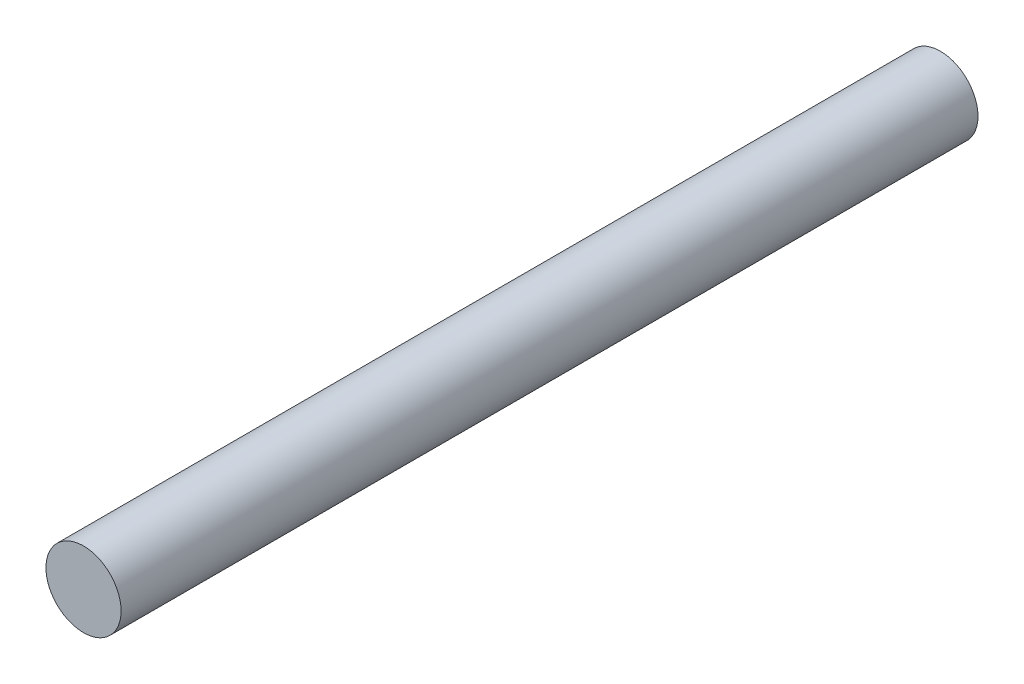
SolidWorks part; units mm, degrees
ref_plane "Front Plane" through (0, 0, 0) normal (0, 0, 1) x (1, 0, 0)
ref_plane "Top Plane" through (0, 0, 0) normal (0, 1, 0) x (1, 0, 0)
ref_plane "Right Plane" through (0, 0, 0) normal (1, 0, 0) x (0, 0, -1)
sketch "Sketch2" plane through (0, 0, 0) normal (0, 0, 1) x (1, 0, 0)
  circle A0 centre (0, 0) radius 0.9716
  point P5 (0, 0)
  dimension "D1" = 1.9431
extrude "Boss-Extrude2" add sketch "Sketch2" along normal blind 22.1488
